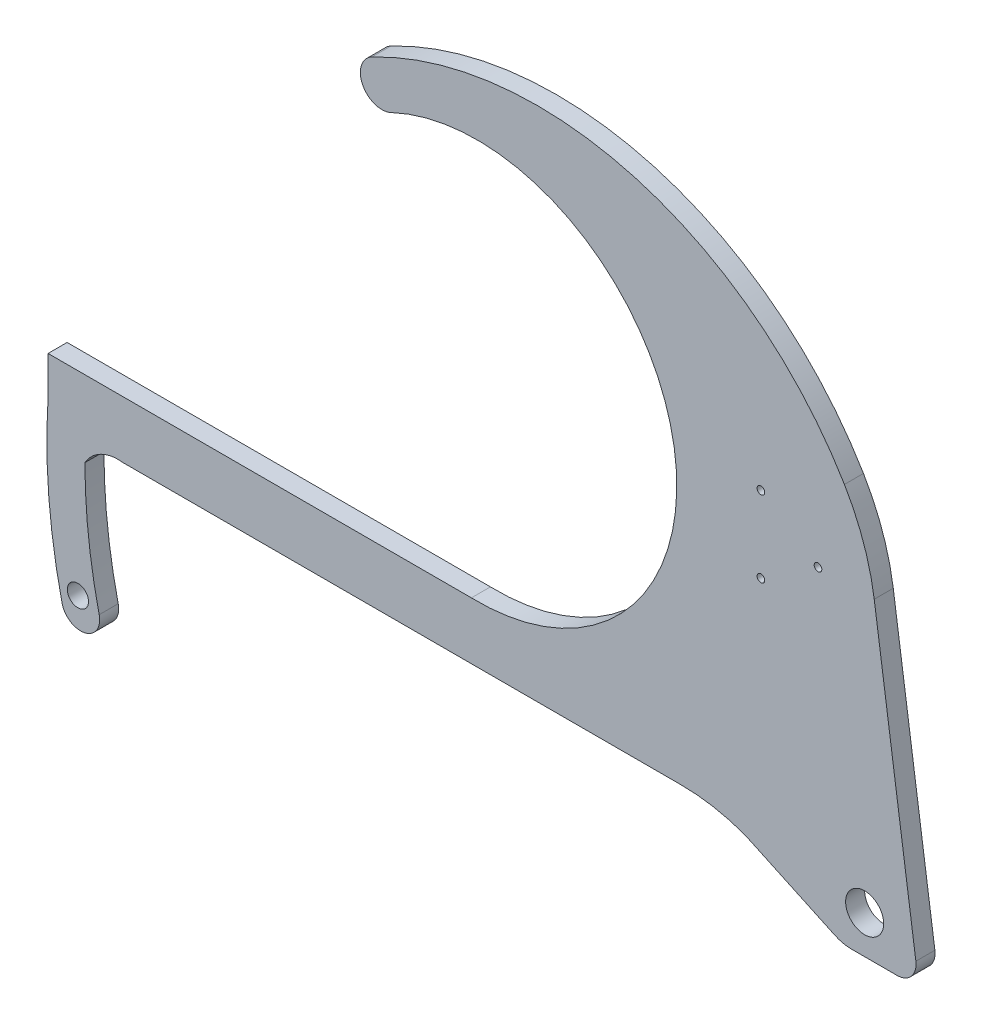
SolidWorks part; units mm, degrees
ref_plane "Front Plane" through (0, 0, 0) normal (0, 0, 1) x (1, 0, 0)
ref_plane "Top Plane" through (0, 0, 0) normal (0, 1, 0) x (1, 0, 0)
ref_plane "Right Plane" through (0, 0, 0) normal (1, 0, 0) x (0, 0, -1)
sketch "Sketch12" plane through (0, 0, 0) normal (0, 0, 1) x (1, 0, 0)
  line L0 (-39.821, 2.4743) -> (-9.8314, -11.5101)
  line L1 (-4.4641, -12.7) -> (10.803, -12.7)
  line L2 (17.0897, -5.4556) -> (1.5957, 103.4523)
  line L4 (-131.2267, 25.4) -> (-272.4912, 25.4)
  line L5 (-272.4912, 25.4) -> (-272.4912, 12.7)
  line L6 (-247.4976, 6.35) -> (-61.685, 6.35)
  circle A0 centre (-262.5344, -39.5986) radius 3.5348
  circle A1 centre (0, 0) radius 6.35
  arc A2 (-9.8314, -11.5101) -> (-4.4641, -12.7) centre (-4.4641, 0) ccw
  arc A3 (10.803, -12.7) -> (17.0897, -5.4556) centre (10.803, -6.35) ccw
  arc A4 (1.5957, 103.4523) -> (-164.4407, 165.0959) centre (-109.1736, 59.5267) ccw
  arc A7 (-131.2267, 25.4) -> (-158.0223, 152.2486) centre (-129.3597, 92.0489) ccw
  arc A8 (-272.4912, 12.7) -> (-267.8135, -44.45) centre (-76.2, 0) ccw
  arc A9 (-267.8135, -44.45) -> (-255.4381, -41.5792) centre (-261.6258, -43.0146) ccw
  arc A10 (-260.1976, 0) -> (-255.4381, -41.5792) centre (-76.2, 0) ccw
  arc A11 (-247.4976, 6.35) -> (-260.1976, 0) centre (-249.1383, -6.2436) ccw
  arc A12 (-39.821, 2.4743) -> (-61.685, 6.35) centre (-61.2366, -54.7287) ccw
  arc A13 (-164.4407, 165.0959) -> (-158.0223, 152.2486) centre (-161.1097, 158.7331) ccw
  dimension "D2" = 31.75
  dimension "D1" = 119.1609
  dimension "D3" = 19.05
extrude "Boss-Extrude1" add sketch "Sketch12" along normal blind 6.35
fillet "Fillet1" radius 76.2 1 edges at (1.5957, 103.4523, 3.175)
sketch "Sketch13" plane through (0, 0, 6.35) normal (0, 0, 1) x (1, 0, 0)
  circle A1 centre (-15.5676, 92.075) radius 1.27
  circle A2 centre (-34.6176, 104.775) radius 1.27
  circle A3 centre (-34.6176, 79.375) radius 1.27
  dimension "D1" = 2.54
  dimension "D2" = 2.54
  dimension "D3" = 2.54
extrude "Cut-Extrude1" cut sketch "Sketch13" against normal up to next
